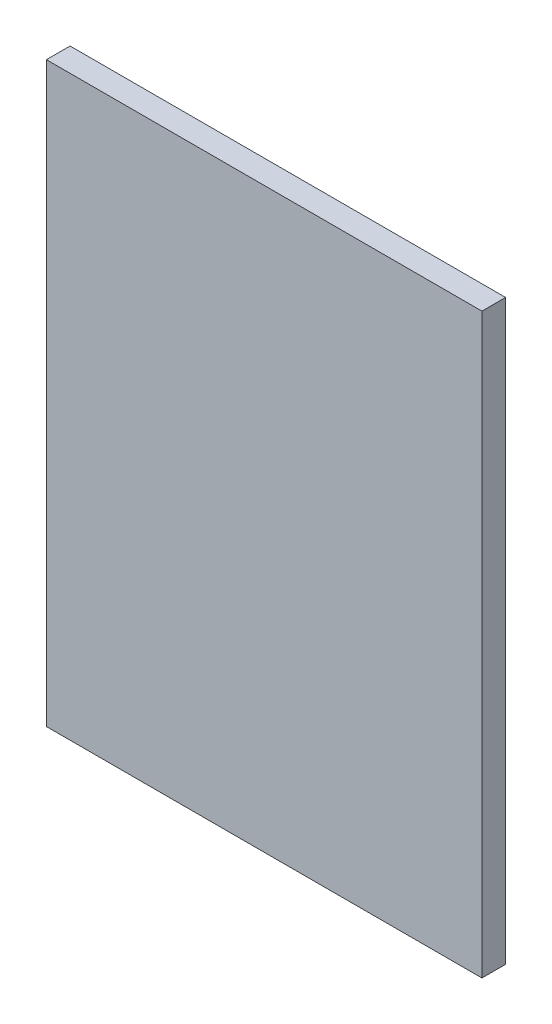
SolidWorks part; units mm, degrees
ref_plane "Front Plane" through (0, 0, 0) normal (0, 0, 1) x (1, 0, 0)
ref_plane "Top Plane" through (0, 0, 0) normal (0, 1, 0) x (1, 0, 0)
ref_plane "Right Plane" through (0, 0, 0) normal (1, 0, 0) x (0, 0, -1)
sketch "Sketch1" plane through (0, 0, 0) normal (0, 0, 1) x (1, 0, 0)
  line L1 (11.8639, 0) -> (471.8639, 0)
  line L2 (11.8639, 0) -> (11.8639, -610)
  line L3 (11.8639, -610) -> (471.8639, -610)
  line L4 (471.8639, 0) -> (471.8639, -610)
  dimension "D1" = 610
  dimension "D2" = 460
extrude "Boss-Extrude1" add sketch "Sketch1" along normal blind 25
sketch "Sketch2" plane through (11.8639, 0, 0) normal (-1, 0, 0) x (0, 0, 1)
  line L0 (0, 0) -> (0, -610) construction
  line L1 (25, -610) -> (0, -610) construction
  circle A0 centre (-37.5, -510) radius 37.5
  dimension "D1" = 75
  dimension "D2" = 37.5
  dimension "D3" = 100
extrude "Boss-Extrude2" add sketch "Sketch2" against normal blind 100 from offset 50 separate body offset against normal yes
sketch "Sketch3" plane through (161.8639, 0, 0) normal (1, 0, 0) x (0, 0, -1)
  circle A0 centre (37.5, -510) radius 10
extrude "Boss-Extrude3" add sketch "Sketch3" along normal blind 100
sketch "Sketch4" plane through (261.8639, 0, 0) normal (1, 0, 0) x (0, 0, -1)
  circle A0 centre (37.5, -510) radius 22.1394
extrude "Boss-Extrude4" add sketch "Sketch4" along normal blind 30 from offset 50 offset against normal yes
sketch "Sketch5" plane through (11.8639, 0, 0) normal (-1, 0, 0) x (0, 0, 1)
  line L0 (0, 0) -> (0, -610) construction
  line L1 (0, -175) -> (-75, -175)
  line L2 (0, -175) -> (0, -100)
  line L3 (0, -100) -> (-75, -100)
  line L4 (-75, -175) -> (-75, -100)
  line L5 (25, 0) -> (0, 0) construction
  circle A0 centre (-37.5, -137.5) radius 15
  dimension "D3" = 100
  dimension "D1" = 75
  dimension "D2" = 75
  dimension "D4" = 37.5
extrude "Boss-Extrude5" add sketch "Sketch5" against normal blind 50 from offset 200 contours L2 L1 L4 L3 | A0 offset against normal yes
fillet "Fillet1" radius 20 2 edges at (236.8639, -100, -75) (236.8639, -175, -75)
